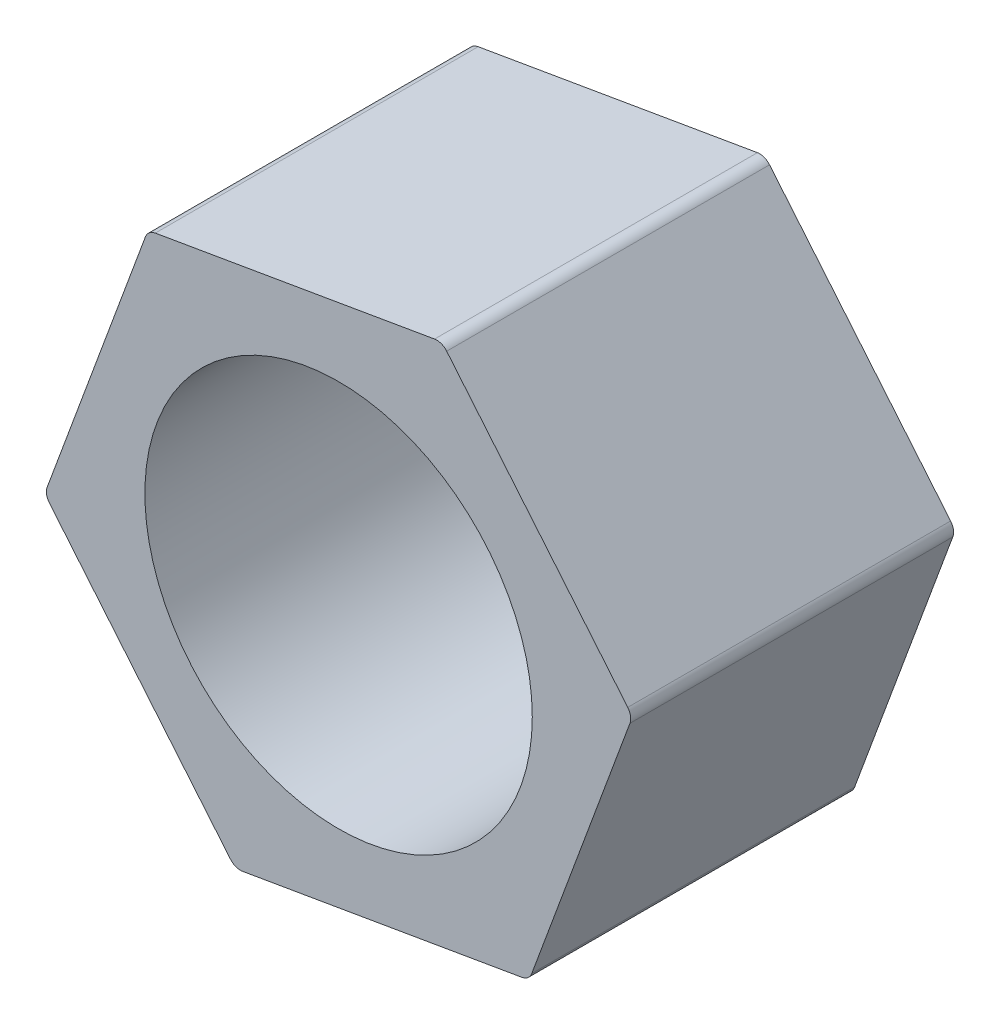
SolidWorks part; units mm, degrees
ref_plane "Front Plane" through (0, 0, 0) normal (0, 0, 1) x (1, 0, 0)
ref_plane "Top Plane" through (0, 0, 0) normal (0, 1, 0) x (1, 0, 0)
ref_plane "Right Plane" through (0, 0, 0) normal (1, 0, 0) x (0, 0, -1)
sketch "Sketch1" plane through (0, 0, 0) normal (0, 0, 1) x (1, 0, 0)
  line L1 (46.192, -3.4441) -> (47.7124, 0.6719)
  line L2 (47.6786, 0.8691) -> (44.8743, 4.2438)
  line L3 (44.6867, 4.3131) -> (40.3619, 3.5719)
  line L4 (40.208, 3.4441) -> (38.6876, -0.6719)
  line L5 (38.7214, -0.8691) -> (41.5257, -4.2438)
  line L6 (41.7133, -4.3131) -> (46.0381, -3.5719)
  circle A0 centre (43.2, 0) radius 3
  circle A1 centre (43.2, 0) radius 3 construction
  circle A2 centre (43.2, 0) radius 4 construction
  arc A3 (41.5257, -4.2438) -> (41.7133, -4.3131) centre (41.6795, -4.116) ccw
  arc A4 (38.6876, -0.6719) -> (38.7214, -0.8691) centre (38.8752, -0.7413) ccw
  arc A5 (40.3619, 3.5719) -> (40.208, 3.4441) centre (40.3957, 3.3748) ccw
  arc A6 (44.8743, 4.2438) -> (44.6867, 4.3131) centre (44.7205, 4.116) ccw
  arc A7 (47.7124, 0.6719) -> (47.6786, 0.8691) centre (47.5248, 0.7413) ccw
  arc A8 (46.192, -3.4441) -> (46.0381, -3.5719) centre (46.0043, -3.3748) cw
  point P5 (40.1236, -2.5565)
  dimension "D2" = 0.2
  dimension "D1" = 8
extrude "Boss-Extrude1" add sketch "Sketch1" along normal blind 5 contours L3 A5 L4 A4 L5 A3 L6 A8 L1 A7 L2 A6 | A0
